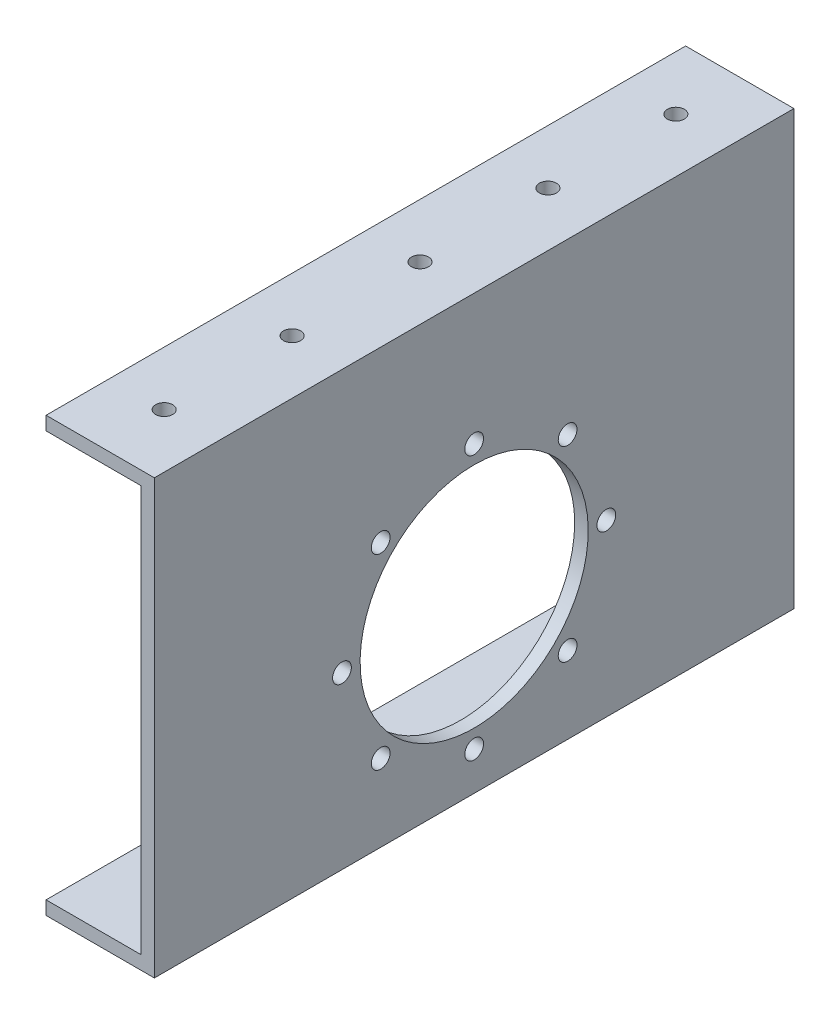
SolidWorks part; units mm, degrees
ref_plane "Front Plane" through (0, 0, 0) normal (0, 0, 1) x (1, 0, 0)
ref_plane "Top Plane" through (0, 0, 0) normal (0, 1, 0) x (1, 0, 0)
ref_plane "Right Plane" through (0, 0, 0) normal (1, 0, 0) x (0, 0, -1)
sketch "Sketch1" plane through (0, 0, 0) normal (0, 0, 1) x (1, 0, 0)
  line L0 (0, 78.4634) -> (25.4, 78.4634)
  line L1 (25.4, 78.4634) -> (25.4, -23.1366)
  line L2 (25.4, -23.1366) -> (0, -23.1366)
  line L3 (0, 75.2884) -> (22.225, 75.2884)
  line L4 (22.225, 75.2884) -> (22.225, -19.9616)
  line L5 (22.225, -19.9616) -> (0, -19.9616)
  line L6 (0, 78.4634) -> (0, 75.2884)
  line L7 (0, -23.1366) -> (0, -19.9616)
  dimension "D1" = 25.4
  dimension "D2" = 101.6
  dimension "D3" = 25.4
  dimension "D4" = 3.175
extrude "Boss-Extrude1" add sketch "Sketch1" along normal blind 150
sketch "Sketch2" plane through (25.4, 0, 0) normal (1, 0, 0) x (0, 0, -1)
  line L0 (-150, -23.1366) -> (0, -23.1366) construction
  line L1 (-150, -23.1366) -> (-150, 78.4634) construction
  circle A0 centre (-75, 16.8634) radius 26.75
  circle A1 centre (-75, 47.8634) radius 2.2
  circle A2 centre (-53.0797, 38.7837) radius 2.2
  circle A3 centre (-44, 16.8634) radius 2.2
  circle A4 centre (-53.0797, -5.0569) radius 2.2
  circle A5 centre (-75, -14.1366) radius 2.2
  circle A6 centre (-96.9203, -5.0569) radius 2.2
  circle A7 centre (-106, 16.8634) radius 2.2
  circle A8 centre (-96.9203, 38.7837) radius 2.2
  point P8 (0, 0)
  point P23 (-75, 16.8634)
  dimension "D1" = 40
  dimension "D2" = 31
  dimension "D4" = 75
  dimension "D5" = 44
  dimension "D3" = 8
extrude "Cut-Extrude1" cut sketch "Sketch2" against normal up to surface (3.175 mm away) up to face at (22.225, 27.6634, 75)
sketch "Sketch3" plane through (0, 78.4634, 0) normal (0, 1, 0) x (1, 0, 0)
  line L0 (12.7, 0) -> (12.7, -150) construction
  line L1 (25.4, 0) -> (0, 0) construction
  line L2 (25.4, -150) -> (0, -150) construction
  circle A0 centre (12.7, -75) radius 2
  circle A1 centre (12.7, -105) radius 2
  circle A2 centre (12.7, -135) radius 2
  circle A3 centre (12.7, -45) radius 2
  circle A4 centre (12.7, -15) radius 2
  dimension "D1" = 3
  dimension "D2" = 3
extrude "Cut-Extrude2" cut sketch "Sketch3" against normal up to surface (101.6 mm away) up to face at (12.7, -23.1366, 75)
